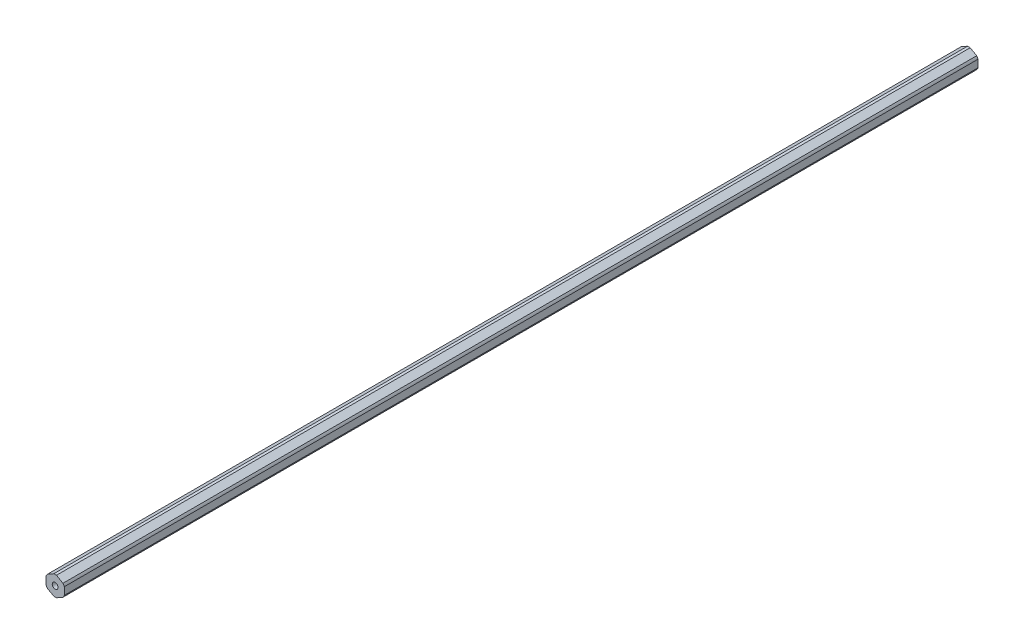
SolidWorks part; units mm, degrees
ref_plane "Front Plane" through (0, 0, 0) normal (0, 0, 1) x (1, 0, 0)
ref_plane "Top Plane" through (0, 0, 0) normal (0, 1, 0) x (1, 0, 0)
ref_plane "Right Plane" through (0, 0, 0) normal (1, 0, 0) x (0, 0, -1)
sketch "Sketch1" plane through (0, 0, 0) normal (0, 0, 1) x (1, 0, 0)
  line L1 (0, 7.3323) -> (-6.35, 3.6662)
  line L2 (-6.35, 3.6662) -> (-6.35, -3.6662)
  line L3 (-6.35, -3.6662) -> (0, -7.3323)
  line L4 (0, -7.3323) -> (6.35, -3.6662)
  line L5 (6.35, -3.6662) -> (6.35, 3.6662)
  line L6 (6.35, 3.6662) -> (0, 7.3323)
  circle A0 centre (0, 0) radius 6.35 construction
  circle A1 centre (0, 0) radius 6.858
  dimension "D1" = 12.7
  dimension "D2" = 13.716
extrude "Boss-Extrude1" add sketch "Sketch1" along normal mid plane 635 contours L5 A1 L6 L1 L2 L3 L4
hole_wizard "#10-32 Tapped Hole1" positions "3DSketch1" profile "Sketch2" tap size "#10-32" standard "ANSI Inch"
sketch3d "3DSketch1"
  line L0 (0, 0, 317.5) -> (0, 0, -317.5) construction
  line L1 (0, 0, 317.5) -> (0, 0, -317.5) construction
  point P0 (0, 0, 317.5)
  point P4 (0, 0, -317.5)
sketch "Sketch2" plane through (0, 0, 317.5) normal (1, 0, 0) x (0, -1, 0)
  line L0 (0, 0) -> (0, 13.1513)
  line L1 (0, 13.1513) -> (2.0193, 11.938)
  line L2 (2.0193, 11.938) -> (2.0193, 0)
  line L5 (2.0193, 0) -> (0, 0)
  line L10 (0, 13.1513) -> (-2.0193, 11.938) construction
  line L11 (0, -6.35) -> (0, 107.95) construction
  dimension "Tap Drill Dia." = 4.0386
  dimension "Tap Drill Depth" = 11.938
  dimension "Drill Angle" = 118
cosmetic thread "Hole Thread1" parameters "D1"=9.652, "D2"=4.826
cosmetic thread "Hole Thread2" parameters "D1"=9.652, "D2"=4.826
